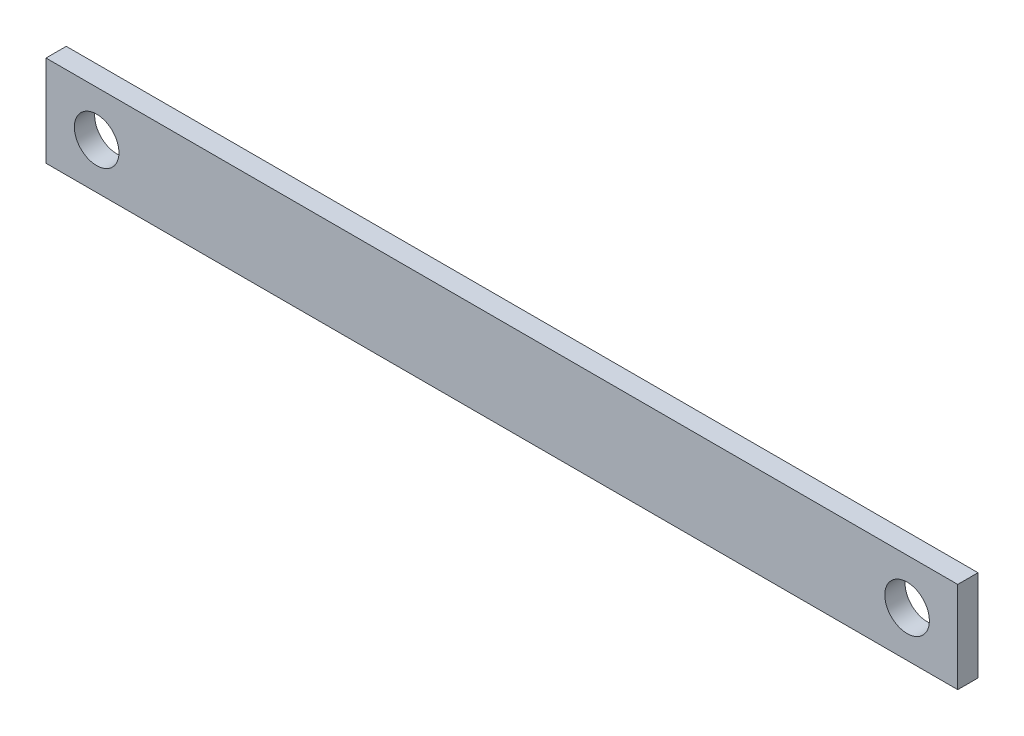
SolidWorks part; units mm, degrees
ref_plane "Front Plane" through (0, 0, 0) normal (0, 0, 1) x (1, 0, 0)
ref_plane "Top Plane" through (0, 0, 0) normal (0, 1, 0) x (1, 0, 0)
ref_plane "Right Plane" through (0, 0, 0) normal (1, 0, 0) x (0, 0, -1)
sketch "Sketch1" plane through (0, 0, 0) normal (0, 0, 1) x (1, 0, 0)
  line L3 (0, 2.54) -> (0, 16.409)
  line L4 (-57.15, 2.54) -> (-57.15, -2.54)
  line L6 (57.15, 2.54) -> (57.15, -2.54)
  line L9 (57.15, 2.54) -> (57.15, 5.715)
  line L10 (-57.15, 2.54) -> (-57.15, 5.715)
  line L11 (0, 0) -> (6.9271, 0)
  line L12 (57.15, -2.54) -> (57.15, -5.715)
  line L13 (-57.15, -2.54) -> (-57.15, -5.715)
  line L14 (-57.15, 5.715) -> (57.15, 5.715)
  line L15 (57.15, -5.715) -> (-57.15, -5.715)
  circle A0 centre (50.8, 0) radius 2.794
  circle A1 centre (-50.8, 0) radius 2.794
  point P4 (0, 0)
  dimension "D2" = 5.588
  dimension "D3" = 5.588
  dimension "D1" = 101.6
  dimension "D5" = 3.175
  dimension "D6" = 3.175
extrude "Boss-Extrude1" add sketch "Sketch1" along normal blind 2.54
sketch "Sketch2" plane through (0, 5.715, 0) normal (0, 1, 0) x (1, 0, 0)
  line L0 (-57.15, 0) -> (-57.15, -2.54)
  line L1 (-57.15, 0) -> (57.0574, 0)
  line L2 (-57.15, -2.54) -> (57.0574, -2.54)
  line L3 (57.0574, 0) -> (57.0574, -2.54)
